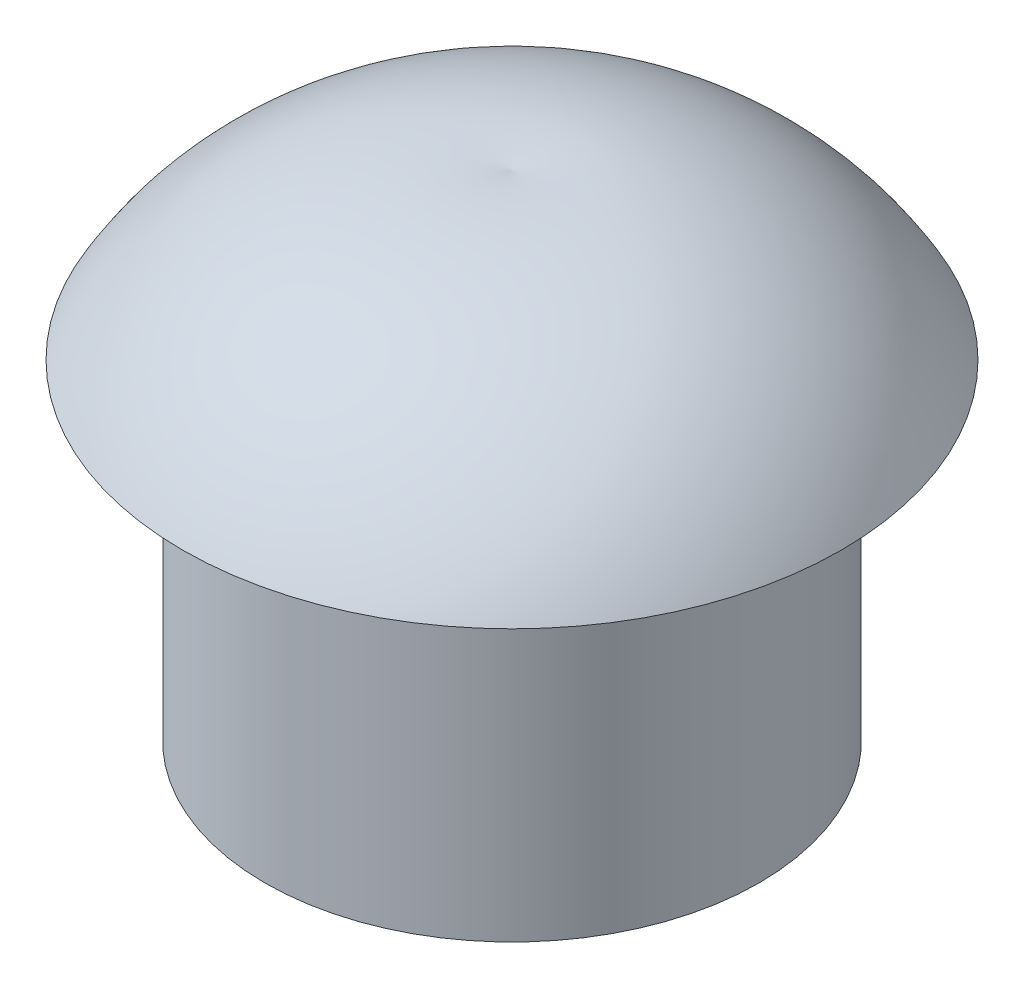
SolidWorks part; units mm, degrees
material "Plain Carbon Steel"
ref_plane "Front Plane" through (0, 0, 0) normal (0, 0, 1) x (1, 0, 0)
ref_plane "Top Plane" through (0, 0, 0) normal (0, 1, 0) x (1, 0, 0)
ref_plane "Right Plane" through (0, 0, 0) normal (1, 0, 0) x (0, 0, -1)
sketch "Sketch1" plane through (0, 0, 0) normal (0, 1, 0) x (1, 0, 0)
  circle A0 centre (0, 0) radius 1.5
  dimension "D1" = 3
extrude "Boss-Extrude1" add sketch "Sketch1" against normal blind 2
sketch "Sketch3" plane through (0, 0, 0) normal (0, 0, 1) x (1, 0, 0)
  line L0 (0, 0) -> (2, 0)
  line L1 (0, 0) -> (0, 1)
  arc A0 (2, 0) -> (0, 1) centre (0.2584, -0.9832) ccw
  dimension "D3" = 2
  dimension "D1" = 1
  dimension "D2" = 2
revolve "Revolve1" add sketch "Sketch3" angle 360 about L1
